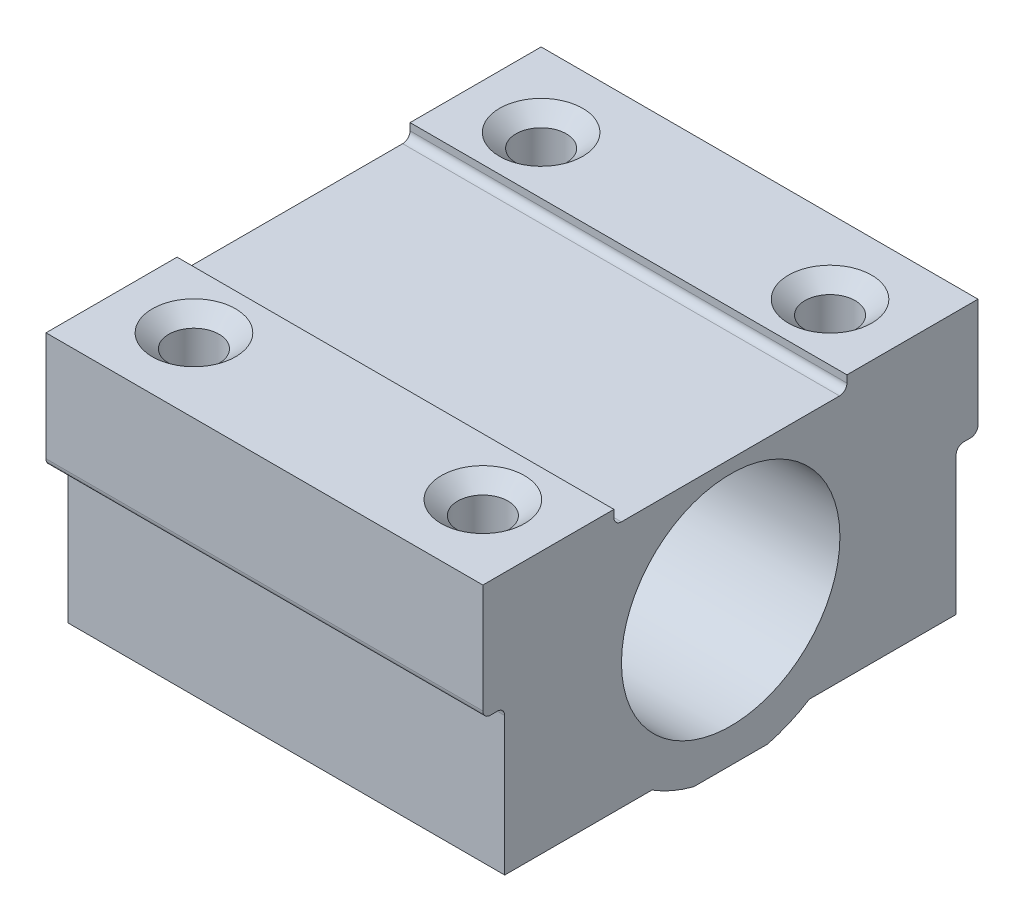
SolidWorks part; units mm, degrees
ref_plane "Front Plane" through (0, 0, 0) normal (0, 0, 1) x (1, 0, 0)
ref_plane "Top Plane" through (0, 0, 0) normal (0, 1, 0) x (1, 0, 0)
ref_plane "Right Plane" through (0, 0, 0) normal (1, 0, 0) x (0, 0, -1)
sketch "Sketch1" plane through (0, 0, 0) normal (1, 0, 0) x (0, 0, -1)
  line L0 (32.5, 0) -> (34, 0)
  line L1 (0, 0) -> (1.5, 0)
  line L2 (0, 0) -> (0, 7.4937)
  line L3 (9, 7) -> (25, 7)
  line L4 (34, 0) -> (34, 7.4937)
  line L6 (1.5, 0) -> (1.5, -10)
  line L7 (1.5, -10) -> (11.6114, -10)
  line L8 (32.5, 0) -> (32.5, -10)
  line L10 (0, 7.4937) -> (0, 8)
  line L11 (0, 8) -> (9, 8)
  line L12 (9, 7) -> (9, 8)
  line L14 (34, 7.4937) -> (34, 8)
  line L15 (34, 8) -> (25, 8)
  line L16 (25, 7) -> (25, 8)
  line L17 (14.4865, -11.2376) -> (19.5495, -11.2376)
  line L18 (22.4246, -10) -> (32.5, -10)
  circle A0 centre (17.018, -1.398) radius 7.5
  arc A1 (11.6114, -10) -> (14.4865, -11.2376) centre (17.018, -1.398) ccw
  arc A2 (19.5495, -11.2376) -> (22.4246, -10) centre (17.018, -1.398) ccw
  point P19 (29.5, 8)
  dimension "D7" = 15
  dimension "D8" = 20.32
  dimension "D1" = 34
  dimension "D2" = 18
  dimension "D3" = 1.5
  dimension "D4" = 10
  dimension "D5" = 1
  dimension "D6" = 9
  dimension "D9" = 9.398
  dimension "D10" = 17.018
extrude "Boss-Extrude1" add sketch "Sketch1" along normal blind 30
hole_wizard "CSK for #4 Flat Head Machine Screw (100)1" positions "Sketch3" profile "Sketch4" countersink size "#4" standard "ANSI Inch"
sketch "Sketch3" plane through (0, 8, 0) normal (0, 1, 0) x (1, 0, 0)
  line L0 (0, 34) -> (0, 25) construction
  line L1 (30, 34) -> (0, 34) construction
  line L2 (30, 0) -> (0, 0) construction
  line L3 (30, 9) -> (30, 0) construction
  point P0 (5.08, 28.92)
  point P2 (24.92, 28.92)
  point P4 (24.92, 5.08)
  point P6 (5.08, 5.08)
  dimension "D1" = 5.08
  dimension "D2" = 5.08
  dimension "D3" = 5.08
  dimension "D4" = 5.08
sketch "Sketch4" plane through (5.08, 8, -28.92) normal (1, 0, 0) x (0, 0, 1)
  line L0 (0, 0) -> (0, 7.3878)
  line L1 (0, 7.3878) -> (1.7272, 6.35)
  line L2 (1.7272, 6.35) -> (1.7272, 0.9484)
  line L3 (1.7272, 0.9484) -> (2.8575, 0)
  line L5 (2.8575, 0) -> (0, 0)
  line L6 (-1.7272, 0.9484) -> (-2.8575, 0) construction
  line L10 (0, 7.3878) -> (-1.7272, 6.35) construction
  line L11 (0, -6.35) -> (0, 107.95) construction
  dimension "Hole Dia." = 3.4544
  dimension "Hole Depth" = 6.35
  dimension "Near C'Sink Dia." = 5.715
  dimension "Near C'Sink Angle" = 100
  dimension "Drill Angle" = 118
fillet "Fillet1" radius 0.508 6 edges at (15, 7, -25) (15, 7, -9) (15, 0, -34) (15, 0, -32.5) (15, 0, 0) (15, 0, -1.5)
